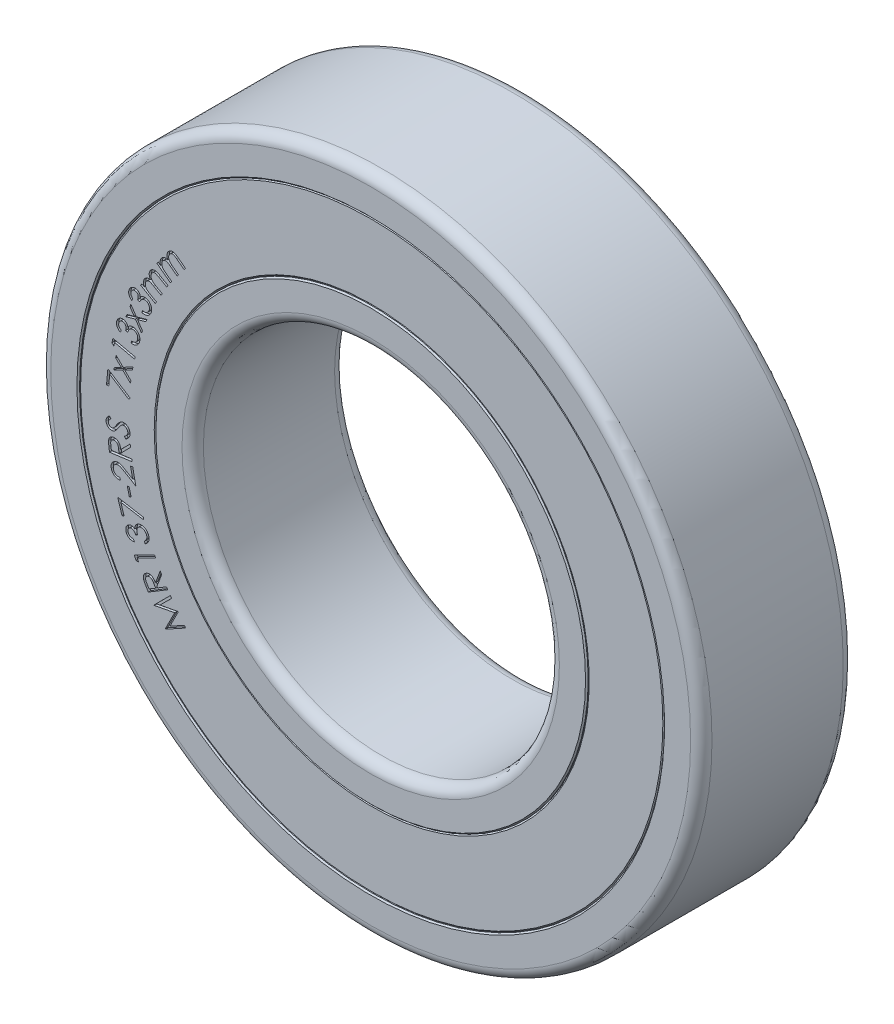
SolidWorks part; units mm, degrees
material "AISI 316 Annealed Stainless Steel Bar (SS)"
ref_plane "Front" through (0, 0, 0) normal (0, 0, 1) x (1, 0, 0)
ref_plane "Top" through (0, 0, 0) normal (0, 1, 0) x (1, 0, 0)
ref_plane "Right" through (0, 0, 0) normal (1, 0, 0) x (0, 0, -1)
sketch "LAYOUT R" plane through (0, 0, 0) normal (1, 0, 0) x (0, 0, -1)
  line L0 (-1.5, 3.5) -> (1.5, 3.5)
  line L1 (1.5, -6.5) -> (-1.5, -6.5) construction
  line L2 (1.5, -6.5) -> (1.5, 6.5) construction
  line L3 (1.5, 6.5) -> (-1.5, 6.5)
  line L4 (-1.5, -6.5) -> (-1.5, 6.5) construction
  line L5 (1.5, -6.5) -> (-1.5, 6.5) construction
  line L6 (1.5, 6.5) -> (-1.5, -6.5) construction
  line L7 (-1.5, 4.25) -> (1.5, 4.25)
  line L8 (-1.5, 5.75) -> (1.5, 5.75)
  line L11 (-17.5, 0) -> (17.5, 0) construction
  line L12 (-1.5, 6.5) -> (-1.5, 5.75)
  line L13 (1.5, 6.5) -> (1.5, 5.75)
  line L14 (-1.5, 5.75) -> (-1.5, 4.25)
  line L15 (1.5, 5.75) -> (1.5, 4.25)
  line L16 (-1.5, 4.25) -> (-1.5, 3.5)
  line L17 (1.5, 4.25) -> (1.5, 3.5)
  line L18 (-1.48, 5.75) -> (-1.48, 4.25)
  line L19 (1.48, 5.75) -> (1.48, 4.25)
  point P0 (0, 0)
  point P15 (0, 0)
  dimension "D1" = 3
  dimension "D2" = 13
  dimension "D3" = 3.5
  dimension "D6" = 0.02
  dimension "D7" = 0.02
  dimension "D4" = 4.25
  dimension "D5" = 5.75
sketch "Sketch R, INNER BODY" plane through (0, 0, 0) normal (1, 0, 0) x (0, 0, -1)
  line L0 (-1.5, 3.5) -> (1.5, 3.5) construction
  line L2 (-1.5, 4.25) -> (1.5, 4.25) construction
  line L4 (-1.5, 3.5) -> (1.5, 3.5)
  line L6 (-1.5, 4.25) -> (1.5, 4.25)
  line L8 (1.5, 4.25) -> (1.5, 3.5) construction
  line L9 (-1.5, 4.25) -> (-1.5, 3.5) construction
  line L10 (1.5, 4.25) -> (1.5, 3.5)
  line L11 (-1.5, 4.25) -> (-1.5, 3.5)
  line L12 (-17.5, 0) -> (17.5, 0) construction
  line L13 (-17.5, 0) -> (17.5, 0) construction
sketch "Sketch R, OUTER BODY" plane through (0, 0, 0) normal (1, 0, 0) x (0, 0, -1)
  line L2 (-1.5, 5.75) -> (1.5, 5.75) construction
  line L3 (1.5, 6.5) -> (-1.5, 6.5) construction
  line L6 (-1.5, 5.75) -> (1.5, 5.75)
  line L7 (1.5, 6.5) -> (-1.5, 6.5)
  line L8 (-17.5, 0) -> (17.5, 0) construction
  line L9 (-17.5, 0) -> (17.5, 0) construction
  line L10 (1.5, 6.5) -> (1.5, 5.75) construction
  line L11 (-1.5, 6.5) -> (-1.5, 5.75) construction
  line L12 (1.5, 6.5) -> (1.5, 5.75)
  line L13 (-1.5, 6.5) -> (-1.5, 5.75)
sketch "Sketch R, SEAL FACES" plane through (0, 0, 0) normal (1, 0, 0) x (0, 0, -1)
  line L0 (-17.5, 0) -> (17.5, 0) construction
  line L1 (-17.5, 0) -> (17.5, 0) construction
  line L3 (-1.5, 4.25) -> (1.5, 4.25) construction
  line L5 (-1.5, 5.75) -> (1.5, 5.75) construction
  line L7 (-1.48, 4.25) -> (1.48, 4.25)
  line L9 (-1.48, 5.75) -> (1.48, 5.75)
  line L10 (1.48, 5.75) -> (1.48, 4.25) construction
  line L11 (-1.48, 5.75) -> (-1.48, 4.25) construction
  line L12 (1.48, 5.75) -> (1.48, 4.25)
  line L13 (-1.48, 5.75) -> (-1.48, 4.25)
revolve "Revolve INNER BODY" add sketch "Sketch R, INNER BODY" angle 360 about L13
fillet "Fillet INNER BODY" radius 0.21 2 edges at (3.5, 0, 1.5) (3.5, 0, -1.5)
chamfer "Chamfer INNER BODY" distance 0.026 angle 45 2 edges at (4.25, 0, -1.5) (4.25, 0, 1.5)
revolve "Revolve OUTER BODY" add sketch "Sketch R, OUTER BODY" angle 360 about L9
fillet "Fillet OUTER BODY" radius 0.21 2 edges at (6.5, 0, -1.5) (6.5, 0, 1.5)
chamfer "Chamfer OUTER BODY" distance 0.026 angle 45 2 edges at (5.75, 0, 1.5) (5.75, 0, -1.5)
revolve "Revolve SEALS" add sketch "Sketch R, SEAL FACES" angle 360 about L1
chamfer "Chamfer SEALS" distance 0.026 angle 45 4 edges at (4.25, 0, -1.48) (5.75, 0, -1.48) (5.75, 0, 1.48) (4.25, 0, 1.48)
sketch "Sketch TEXT RADIUS 1 — MANUALLY ASSIGN TEXT AND FONT SIZE (FROM EQUATIONS)" plane through (0, 0, 1.48) normal (0, 0, 1) x (1, 0, 0)
  circle A0 centre (0, 0) radius 4.775 construction
  text T0 "MR137-2RS  7x13x3mm" font "Century Gothic" height 0.45
  dimension "D1" = 9.55
extrude "Cut-Extrude SEAL LABEL 1" cut sketch "Sketch TEXT RADIUS 1 — MANUALLY ASSIGN TEXT AND FONT SIZE (FROM EQUATIONS)" against normal blind 0.05
sketch "Sketch TEXT RADIUS 2 — MANUALLY ASSIGN TEXT AND FONT SIZE (FROM EQUATIONS)" plane through (0, 0, -1.48) normal (0, 0, -1) x (-1, 0, 0)
  circle A0 centre (0, 0) radius 4.775 construction
  text T0 "MR137-2RS  7x13x3mm" font "Century Gothic" height 0.45
  dimension "D1" = 9.55
extrude "Cut-Extrude SEAL LABEL 2" cut sketch "Sketch TEXT RADIUS 2 — MANUALLY ASSIGN TEXT AND FONT SIZE (FROM EQUATIONS)" against normal blind 0.05
equation "\"_i__BORE\"= 7"
equation "\"_i__OUTSIDE_DIAMETER\"= 13"
equation "\"_i__WIDTH\"= 3"
equation "\"_i_optional__TEXT_RADIUS_ADJUSTMENT\"= 0"
equation "\"_output__FONT_SIZE_mm\"= \"BODY_SPAN__SEAL__OF_RADIUS\" * \"param__FONT_SIZE_RATIO\"'MANUALLY ASSIGN TO FONT"
equation "\"BODY__HALF_WIDTH\"= \"_i__WIDTH\" / 2"
equation "\"BODY_SPAN___OF_DIAMETER\"= \"_i__OUTSIDE_DIAMETER\" - \"_i__BORE\""
equation "\"BODY_SPAN___OF_RADIUS\"= \"BODY_SPAN___OF_DIAMETER\" / 2"
equation "\"BODY_SPAN__BORE_AND_OD__OF RADIUS\"= ( \"BODY_SPAN___OF_RADIUS\" - \"BODY_SPAN__SEAL__OF_RADIUS\" ) / 2"
equation "\"BODY_SPAN__SEAL__OF_RADIUS\"= \"BODY_SPAN___OF_RADIUS\" * \"param__SEAL_PANEL_SPAN__RATIO_OF_BODY_RADIAN\""
equation "\"BORE__RADIUS\"= \"_i__BORE\" / 2"
equation "\"CORNER_RADII\"= \"_i__WIDTH\" * \"param__CORNER_RADII__ISO_MAX_RATIO_TO_WIDTH\""
equation "\"param__CORNER_RADII__ISO_MAX_RATIO_TO_WIDTH\"= 0.07'WHERE WIDTH IS LESS THAN DIAMETER"
equation "\"param__FONT_SIZE_RATIO\"= 0.3"
equation "\"param__SEAL_FACE_INSET__RATIO_OF_WIDTH\"= .01"
equation "\"param__SEAL_PANEL_SPAN__RATIO_OF_BODY_RADIAN\"= 0.5"
equation "\"param__SIDE_CHAMFERS__RATIO_TO_OD\"= 1 / 500"
equation "\"RING_INNER__OUTSIDE_RADIUS\"= \"BORE__RADIUS\" + \"BODY_SPAN__BORE_AND_OD__OF RADIUS\""
equation "\"RING_OUTER__OUTSIDE_RADIUS\"= ( \"_i__OUTSIDE_DIAMETER\" / 2 ) - \"BODY_SPAN__BORE_AND_OD__OF RADIUS\""
equation "\"SEAL_FACE_INSET\"= \"_i__WIDTH\" * \"param__SEAL_FACE_INSET__RATIO_OF_WIDTH\""
equation "\"SIDE_FACE_AND_SEAL_CHAMFERS\"= \"_i__OUTSIDE_DIAMETER\" * \"param__SIDE_CHAMFERS__RATIO_TO_OD\""
equation "\"TEXT_RADIUS\"= \"_i__BORE\" + ( \"BODY_SPAN___OF_DIAMETER\" / 2 ) - \"_output__FONT_SIZE_mm\" + \"_i_optional__TEXT_RADIUS_ADJUSTMENT\""
equation "\"D1@Chamfer INNER BODY\"=\"SIDE_FACE_AND_SEAL_CHAMFERS\""
equation "\"D1@Chamfer OUTER BODY\"=\"SIDE_FACE_AND_SEAL_CHAMFERS\""
equation "\"D1@Chamfer SEALS\"=\"SIDE_FACE_AND_SEAL_CHAMFERS\""
equation "\"D1@Fillet INNER BODY\"=\"CORNER_RADII\""
equation "\"D1@Fillet OUTER BODY\"=\"CORNER_RADII\""
equation "\"D1@LAYOUT R\"=\"_i__WIDTH\""
equation "\"D1@Sketch TEXT RADIUS 1 — MANUALLY ASSIGN TEXT AND FONT SIZE (FROM EQUATIONS)\" = \"TEXT_RADIUS\""
equation "\"D1@Sketch TEXT RADIUS 2 — MANUALLY ASSIGN TEXT AND FONT SIZE (FROM EQUATIONS)\" = \"TEXT_RADIUS\""
equation "\"D2@LAYOUT R\"=\"_i__OUTSIDE_DIAMETER\""
equation "\"D3@LAYOUT R\"=\"BORE__RADIUS\""
equation "\"D4@LAYOUT R\"=\"RING_INNER__OUTSIDE_RADIUS\""
equation "\"D5@LAYOUT R\"=\"RING_OUTER__OUTSIDE_RADIUS\""
